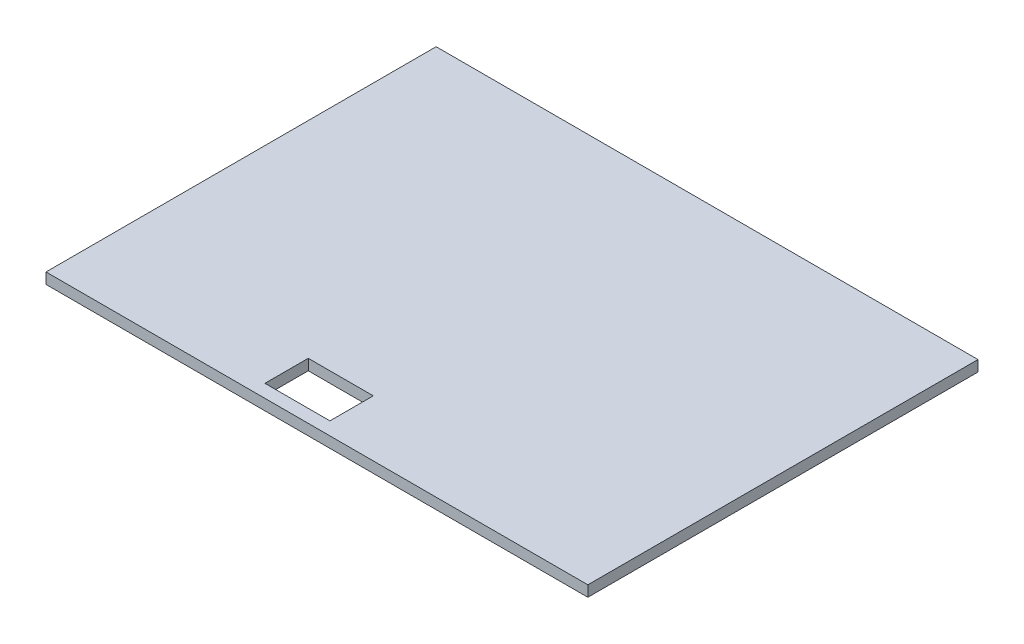
SolidWorks part; units mm, degrees
ref_plane "Front Plane" through (0, 0, 0) normal (0, 0, 1) x (1, 0, 0)
ref_plane "Top Plane" through (0, 0, 0) normal (0, 1, 0) x (1, 0, 0)
ref_plane "Right Plane" through (0, 0, 0) normal (1, 0, 0) x (0, 0, -1)
sketch "Sketch1" plane through (0, 0, 0) normal (0, 1, 0) x (1, 0, 0)
  line L1 (62.5, -45) -> (-62.5, -45)
  line L2 (62.5, -45) -> (62.5, 45)
  line L3 (62.5, 45) -> (-62.5, 45)
  line L4 (-62.5, -45) -> (-62.5, 45)
  line L5 (62.5, -45) -> (-62.5, 45) construction
  line L6 (62.5, 45) -> (-62.5, -45) construction
  line L7 (-15, -32) -> (0, -32)
  line L8 (-15, -32) -> (-15, -42)
  line L9 (-15, -42) -> (0, -42)
  line L10 (0, -32) -> (0, -42)
  line L11 (-15, -32) -> (0, -42) construction
  line L12 (-15, -42) -> (0, -32) construction
  point P0 (0, 0)
  point P6 (-7.5, -37)
  dimension "D1" = 125
  dimension "D2" = 90
  dimension "D3" = 10
  dimension "D4" = 15
  dimension "D5" = 8
  dimension "D6" = 55
extrude "Boss-Extrude1" add sketch "Sketch1" along normal blind 2.5
